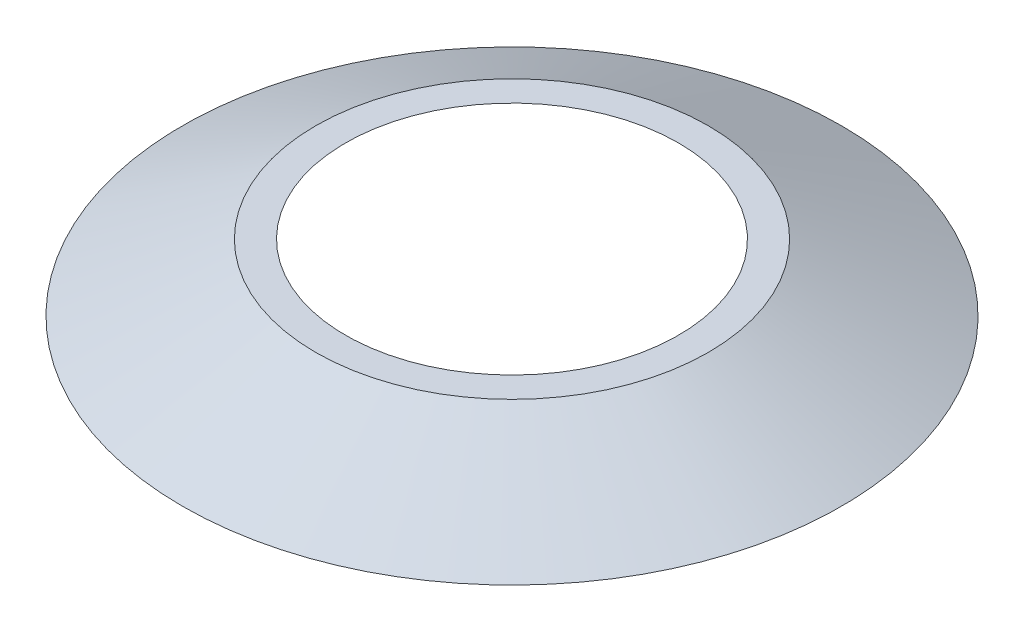
SolidWorks part; units mm, degrees
ref_plane "Ön Düzlem" through (0, 0, 0) normal (0, 0, 1) x (1, 0, 0)
ref_plane "Üst Düzlem" through (0, 0, 0) normal (0, 1, 0) x (1, 0, 0)
ref_plane "Sağ Düzlem" through (0, 0, 0) normal (1, 0, 0) x (0, 0, -1)
sketch "Çizim1" plane through (0, 0, 0) normal (0, 0, 1) x (1, 0, 0)
  line L0 (0, 0) -> (0, 2.2158) construction
  line L1 (-4.5, 0) -> (-2.5, 1)
  line L2 (-2.5, 1) -> (-2.9472, 1)
  line L3 (-2.9472, 1) -> (-4.9472, 0)
  line L4 (-4.9472, 0) -> (-4.5, 0)
  point P5 (-5.5212, 0)
  dimension "D1" = 2.5
  dimension "D2" = 1
  dimension "D3" = 4.5
  dimension "D4" = 0.2
revolve "Döndür1" add sketch "Çizim1" angle 360 about L0
